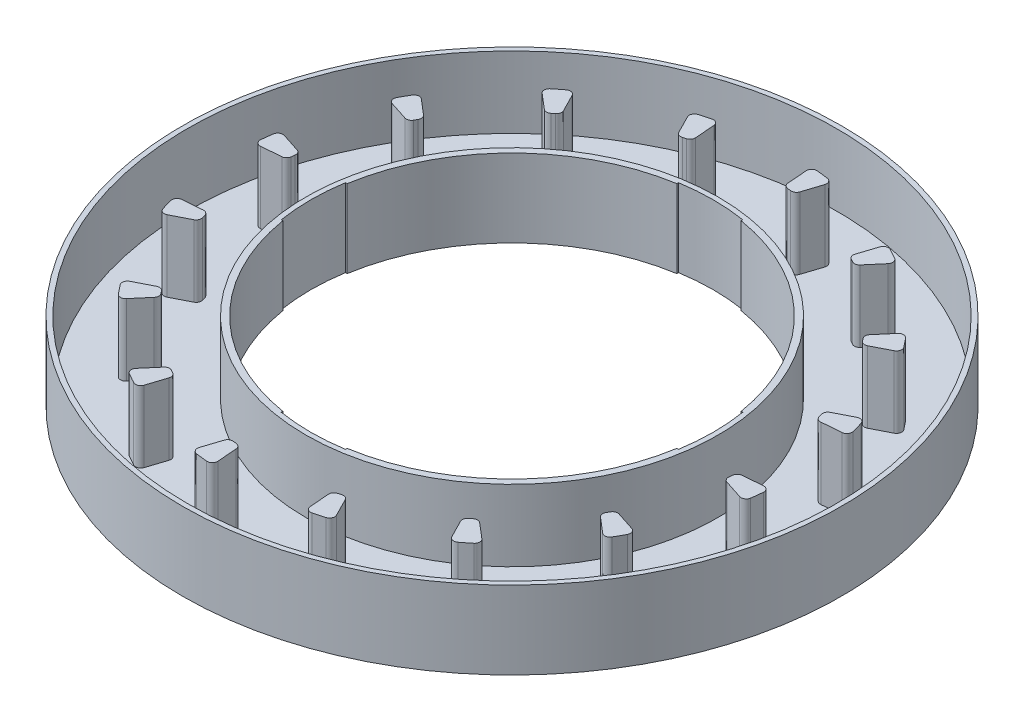
SolidWorks part; units mm, degrees
ref_plane "Front Plane" through (0, 0, 0) normal (0, 0, 1) x (1, 0, 0)
ref_plane "Top Plane" through (0, 0, 0) normal (0, 1, 0) x (1, 0, 0)
ref_plane "Right Plane" through (0, 0, 0) normal (1, 0, 0) x (0, 0, -1)
sketch "Sketch1" plane through (0, 0, 0) normal (0, 1, 0) x (1, 0, 0)
  circle A0 centre (0, 0) radius 61.5
  circle A1 centre (0, 0) radius 101.5
  dimension "D1" = 123
  dimension "D2" = 203
extrude "Boss-Extrude1" add sketch "Sketch1" along normal blind 2
sketch "Sketch2" plane through (0, 2, 0) normal (0, 1, 0) x (1, 0, 0)
  circle A0 centre (0, 0) radius 101.5
  circle A1 centre (0, 0) radius 61.5
  circle A2 centre (0, 0) radius 101.5 construction
  circle A3 centre (0, 0) radius 61.5 construction
  circle A4 centre (0, 0) radius 63.5
  circle A5 centre (0, 0) radius 100
  circle M3 centre (0, 0) radius 101.5
  circle M4 centre (0, 0) radius 61.5
  dimension "D1" = 127
  dimension "D2" = 200
extrude "Boss-Extrude2" add sketch "Sketch2" along normal blind 22 contours A5 M3 | A4 M4
sketch "Sketch3" plane through (0, 0, 0) normal (0, -1, 0) x (1, 0, 0)
  line L0 (-9.8485, 60.7063) -> (-9.9567, 61.1945)
  line L1 (0, 0) -> (0, 124.0373) construction
  line L2 (9.8485, 60.7063) -> (9.9567, 61.1945)
  line L3 (60.7063, -9.8485) -> (61.1945, -9.9567)
  line L4 (60.7063, 9.8485) -> (61.1945, 9.9567)
  line L5 (-9.8485, -60.7063) -> (-9.9567, -61.1945)
  line L6 (9.8485, -60.7063) -> (9.9567, -61.1945)
  line L7 (-60.7063, 9.8485) -> (-61.1945, 9.9567)
  line L8 (-60.7063, -9.8485) -> (-61.1945, -9.9567)
  circle A0 centre (0, 0) radius 61.5 construction
  arc A1 (-9.9567, 61.1945) -> (9.9567, 61.1945) centre (0, 0) cw
  arc A2 (-9.8485, 60.7063) -> (9.8485, 60.7063) centre (0, 0) cw
  arc A3 (60.7063, 9.8485) -> (60.7063, -9.8485) centre (0, 0) cw
  arc A4 (61.1945, 9.9567) -> (61.1945, -9.9567) centre (0, 0) cw
  arc A5 (9.8485, -60.7063) -> (-9.8485, -60.7063) centre (0, 0) cw
  arc A6 (9.9567, -61.1945) -> (-9.9567, -61.1945) centre (0, 0) cw
  arc A7 (-60.7063, -9.8485) -> (-60.7063, 9.8485) centre (0, 0) cw
  arc A8 (-61.1945, -9.9567) -> (-61.1945, 9.9567) centre (0, 0) cw
  point P25 (0, 0)
  dimension "D1" = 25
  dimension "D2" = 20
  dimension "D4" = 4
  dimension "D3" = 0.5
extrude "Cut-Extrude1" cut sketch "Sketch3" against normal through all both and the other way through all
sketch "Sketch4" plane through (0, 2, 0) normal (0, 1, 0) x (1, 0, 0)
  line L2 (64.0409, 54.7617) -> (60.0822, 50.1192)
  line L3 (62.6863, 46.8212) -> (68.1203, 49.5954)
  line L4 (38.2097, 75.1006) -> (36.3289, 69.2965)
  line L5 (39.9969, 67.2462) -> (43.9556, 71.8887)
  line L6 (38.2097, 75.1006) -> (36.3289, 69.2965)
  line L7 (39.9969, 67.2462) -> (43.9556, 71.8887)
  line L8 (80.1225, 26.0858) -> (74.6885, 23.3116)
  line L9 (75.8323, 19.2681) -> (81.9143, 19.7516)
  line L10 (84.0061, -6.5614) -> (77.9241, -7.0449)
  line L11 (77.4335, -11.2183) -> (83.2376, -13.0991)
  line L12 (75.1006, -38.2097) -> (69.2965, -36.3289)
  line L13 (67.2462, -39.9969) -> (71.8887, -43.9556)
  line L14 (54.7617, -64.0409) -> (50.1192, -60.0822)
  line L15 (46.8212, -62.6863) -> (49.5954, -68.1203)
  line L16 (26.0858, -80.1225) -> (23.3116, -74.6885)
  line L17 (19.2681, -75.8323) -> (19.7516, -81.9143)
  line L18 (-6.5614, -84.0061) -> (-7.0449, -77.9241)
  line L19 (-11.2183, -77.4335) -> (-13.0991, -83.2376)
  line L20 (-38.2097, -75.1006) -> (-36.3289, -69.2965)
  line L21 (-39.9969, -67.2462) -> (-43.9556, -71.8887)
  line L22 (-64.0409, -54.7617) -> (-60.0822, -50.1192)
  line L23 (-62.6863, -46.8212) -> (-68.1203, -49.5954)
  line L24 (-80.1225, -26.0858) -> (-74.6885, -23.3116)
  line L25 (-75.8323, -19.2681) -> (-81.9143, -19.7516)
  line L26 (-84.0061, 6.5614) -> (-77.9241, 7.0449)
  line L27 (-77.4335, 11.2183) -> (-83.2376, 13.0991)
  line L28 (-75.1006, 38.2097) -> (-69.2965, 36.3289)
  line L29 (-67.2462, 39.9969) -> (-71.8887, 43.9556)
  line L30 (-54.7617, 64.0409) -> (-50.1192, 60.0822)
  line L31 (-46.8212, 62.6863) -> (-49.5954, 68.1203)
  line L32 (-26.0858, 80.1225) -> (-23.3116, 74.6885)
  line L33 (-19.2681, 75.8323) -> (-19.7516, 81.9143)
  line L34 (6.5614, 84.0061) -> (7.0449, 77.9241)
  line L35 (11.2183, 77.4335) -> (13.0991, 83.2376)
  arc A6 (68.1203, 49.5954) -> (68.6689, 51.9857) centre (67.3928, 51.0204) ccw
  arc A7 (68.6689, 51.9857) -> (66.4933, 54.7409) centre (1.199, 0.9467) ccw
  arc A8 (66.4933, 54.7409) -> (64.0409, 54.7617) centre (65.2584, 53.7235) ccw
  arc A9 (60.0822, 50.1192) -> (60.0508, 48.0808) centre (61.2997, 49.081) ccw
  arc A10 (60.6963, 47.2634) -> (60.0508, 48.0808) centre (1.199, 0.9467) ccw
  arc A11 (60.6963, 47.2634) -> (62.6863, 46.8212) centre (61.9588, 48.2462) ccw
  arc A12 (43.9556, 71.8887) -> (43.5477, 74.307) centre (42.7382, 72.9269) ccw
  arc A13 (43.5477, 74.307) -> (40.4833, 76.0199) centre (0.7454, 1.3335) ccw
  arc A14 (40.4833, 76.0199) -> (38.2097, 75.1006) centre (39.7318, 74.6074) ccw
  arc A15 (36.3289, 69.2965) -> (37.08, 67.4013) centre (37.851, 68.8033) ccw
  arc A16 (37.9891, 66.8931) -> (37.08, 67.4013) centre (0.7454, 1.3335) ccw
  arc A17 (37.9891, 66.8931) -> (39.9969, 67.2462) centre (38.7794, 68.2843) ccw
  arc A18 (43.9556, 71.8887) -> (43.5477, 74.307) centre (42.7382, 72.9269) ccw
  arc A19 (43.5477, 74.307) -> (40.4833, 76.0199) centre (0.7454, 1.3335) ccw
  arc A20 (40.4833, 76.0199) -> (38.2097, 75.1006) centre (39.7318, 74.6074) ccw
  arc A21 (36.3289, 69.2965) -> (37.08, 67.4013) centre (37.851, 68.8033) ccw
  arc A22 (37.9891, 66.8931) -> (37.08, 67.4013) centre (0.7454, 1.3335) ccw
  arc A23 (37.9891, 66.8931) -> (39.9969, 67.2462) centre (38.7794, 68.2843) ccw
  arc A24 (81.9143, 19.7516) -> (83.3358, 21.7501) centre (81.7875, 21.3466) ccw
  arc A25 (83.3358, 21.7501) -> (82.3802, 25.1281) centre (1.47, 0.4158) ccw
  arc A26 (82.3802, 25.1281) -> (80.1225, 26.0858) centre (80.85, 24.6608) ccw
  arc A27 (74.6885, 23.3116) -> (73.8795, 21.4404) centre (75.416, 21.8866) ccw
  arc A28 (74.163, 20.4382) -> (73.8795, 21.4404) centre (1.47, 0.4158) ccw
  arc A29 (74.163, 20.4382) -> (75.8323, 19.2681) centre (75.7055, 20.8631) ccw
  arc A30 (83.2376, -13.0991) -> (85.3157, -11.7968) centre (83.7308, -11.577) ccw
  arc A31 (85.3157, -11.7968) -> (85.7255, -8.3102) centre (1.5173, -0.1784) ccw
  arc A32 (85.7255, -8.3102) -> (84.0061, -6.5614) centre (84.1329, -8.1564) ccw
  arc A33 (77.9241, -7.0449) -> (76.4606, -8.4641) centre (78.0509, -8.6399) ccw
  arc A34 (76.339, -9.4985) -> (76.4606, -8.4641) centre (1.5173, -0.1784) ccw
  arc A35 (76.339, -9.4985) -> (77.4335, -11.2183) centre (77.9267, -9.6962) ccw
  arc A36 (71.8887, -43.9556) -> (74.307, -43.5477) centre (72.9269, -42.7382) ccw
  arc A37 (74.307, -43.5477) -> (76.0199, -40.4833) centre (1.3335, -0.7454) ccw
  arc A38 (76.0199, -40.4833) -> (75.1006, -38.2097) centre (74.6074, -39.7318) ccw
  arc A39 (69.2965, -36.3289) -> (67.4013, -37.08) centre (68.8033, -37.851) ccw
  arc A40 (66.8931, -37.9891) -> (67.4013, -37.08) centre (1.3335, -0.7454) ccw
  arc A41 (66.8931, -37.9891) -> (67.2462, -39.9969) centre (68.2843, -38.7794) ccw
  arc A42 (49.5954, -68.1203) -> (51.9857, -68.6689) centre (51.0204, -67.3928) ccw
  arc A43 (51.9857, -68.6689) -> (54.7409, -66.4933) centre (0.9467, -1.199) ccw
  arc A44 (54.7409, -66.4933) -> (54.7617, -64.0409) centre (53.7235, -65.2584) ccw
  arc A45 (50.1192, -60.0822) -> (48.0808, -60.0508) centre (49.081, -61.2997) ccw
  arc A46 (47.2634, -60.6963) -> (48.0808, -60.0508) centre (0.9467, -1.199) ccw
  arc A47 (47.2634, -60.6963) -> (46.8212, -62.6863) centre (48.2462, -61.9588) ccw
  arc A48 (19.7516, -81.9143) -> (21.7501, -83.3358) centre (21.3466, -81.7875) ccw
  arc A49 (21.7501, -83.3358) -> (25.1281, -82.3802) centre (0.4158, -1.47) ccw
  arc A50 (25.1281, -82.3802) -> (26.0858, -80.1225) centre (24.6608, -80.85) ccw
  arc A51 (23.3116, -74.6885) -> (21.4404, -73.8795) centre (21.8866, -75.416) ccw
  arc A52 (20.4382, -74.163) -> (21.4404, -73.8795) centre (0.4158, -1.47) ccw
  arc A53 (20.4382, -74.163) -> (19.2681, -75.8323) centre (20.8631, -75.7055) ccw
  arc A54 (-13.0991, -83.2376) -> (-11.7968, -85.3157) centre (-11.577, -83.7308) ccw
  arc A55 (-11.7968, -85.3157) -> (-8.3102, -85.7255) centre (-0.1784, -1.5173) ccw
  arc A56 (-8.3102, -85.7255) -> (-6.5614, -84.0061) centre (-8.1564, -84.1329) ccw
  arc A57 (-7.0449, -77.9241) -> (-8.4641, -76.4606) centre (-8.6399, -78.0509) ccw
  arc A58 (-9.4985, -76.339) -> (-8.4641, -76.4606) centre (-0.1784, -1.5173) ccw
  arc A59 (-9.4985, -76.339) -> (-11.2183, -77.4335) centre (-9.6962, -77.9267) ccw
  arc A60 (-43.9556, -71.8887) -> (-43.5477, -74.307) centre (-42.7382, -72.9269) ccw
  arc A61 (-43.5477, -74.307) -> (-40.4833, -76.0199) centre (-0.7454, -1.3335) ccw
  arc A62 (-40.4833, -76.0199) -> (-38.2097, -75.1006) centre (-39.7318, -74.6074) ccw
  arc A63 (-36.3289, -69.2965) -> (-37.08, -67.4013) centre (-37.851, -68.8033) ccw
  arc A64 (-37.9891, -66.8931) -> (-37.08, -67.4013) centre (-0.7454, -1.3335) ccw
  arc A65 (-37.9891, -66.8931) -> (-39.9969, -67.2462) centre (-38.7794, -68.2843) ccw
  arc A66 (-68.1203, -49.5954) -> (-68.6689, -51.9857) centre (-67.3928, -51.0204) ccw
  arc A67 (-68.6689, -51.9857) -> (-66.4933, -54.7409) centre (-1.199, -0.9467) ccw
  arc A68 (-66.4933, -54.7409) -> (-64.0409, -54.7617) centre (-65.2584, -53.7235) ccw
  arc A69 (-60.0822, -50.1192) -> (-60.0508, -48.0808) centre (-61.2997, -49.081) ccw
  arc A70 (-60.6963, -47.2634) -> (-60.0508, -48.0808) centre (-1.199, -0.9467) ccw
  arc A71 (-60.6963, -47.2634) -> (-62.6863, -46.8212) centre (-61.9588, -48.2462) ccw
  arc A72 (-81.9143, -19.7516) -> (-83.3358, -21.7501) centre (-81.7875, -21.3466) ccw
  arc A73 (-83.3358, -21.7501) -> (-82.3802, -25.1281) centre (-1.47, -0.4158) ccw
  arc A74 (-82.3802, -25.1281) -> (-80.1225, -26.0858) centre (-80.85, -24.6608) ccw
  arc A75 (-74.6885, -23.3116) -> (-73.8795, -21.4404) centre (-75.416, -21.8866) ccw
  arc A76 (-74.163, -20.4382) -> (-73.8795, -21.4404) centre (-1.47, -0.4158) ccw
  arc A77 (-74.163, -20.4382) -> (-75.8323, -19.2681) centre (-75.7055, -20.8631) ccw
  arc A78 (-83.2376, 13.0991) -> (-85.3157, 11.7968) centre (-83.7308, 11.577) ccw
  arc A79 (-85.3157, 11.7968) -> (-85.7255, 8.3102) centre (-1.5173, 0.1784) ccw
  arc A80 (-85.7255, 8.3102) -> (-84.0061, 6.5614) centre (-84.1329, 8.1564) ccw
  arc A81 (-77.9241, 7.0449) -> (-76.4606, 8.4641) centre (-78.0509, 8.6399) ccw
  arc A82 (-76.339, 9.4985) -> (-76.4606, 8.4641) centre (-1.5173, 0.1784) ccw
  arc A83 (-76.339, 9.4985) -> (-77.4335, 11.2183) centre (-77.9267, 9.6962) ccw
  arc A84 (-71.8887, 43.9556) -> (-74.307, 43.5477) centre (-72.9269, 42.7382) ccw
  arc A85 (-74.307, 43.5477) -> (-76.0199, 40.4833) centre (-1.3335, 0.7454) ccw
  arc A86 (-76.0199, 40.4833) -> (-75.1006, 38.2097) centre (-74.6074, 39.7318) ccw
  arc A87 (-69.2965, 36.3289) -> (-67.4013, 37.08) centre (-68.8033, 37.851) ccw
  arc A88 (-66.8931, 37.9891) -> (-67.4013, 37.08) centre (-1.3335, 0.7454) ccw
  arc A89 (-66.8931, 37.9891) -> (-67.2462, 39.9969) centre (-68.2843, 38.7794) ccw
  arc A90 (-49.5954, 68.1203) -> (-51.9857, 68.6689) centre (-51.0204, 67.3928) ccw
  arc A91 (-51.9857, 68.6689) -> (-54.7409, 66.4933) centre (-0.9467, 1.199) ccw
  arc A92 (-54.7409, 66.4933) -> (-54.7617, 64.0409) centre (-53.7235, 65.2584) ccw
  arc A93 (-50.1192, 60.0822) -> (-48.0808, 60.0508) centre (-49.081, 61.2997) ccw
  arc A94 (-47.2634, 60.6963) -> (-48.0808, 60.0508) centre (-0.9467, 1.199) ccw
  arc A95 (-47.2634, 60.6963) -> (-46.8212, 62.6863) centre (-48.2462, 61.9588) ccw
  arc A96 (-19.7516, 81.9143) -> (-21.7501, 83.3358) centre (-21.3466, 81.7875) ccw
  arc A97 (-21.7501, 83.3358) -> (-25.1281, 82.3802) centre (-0.4158, 1.47) ccw
  arc A98 (-25.1281, 82.3802) -> (-26.0858, 80.1225) centre (-24.6608, 80.85) ccw
  arc A99 (-23.3116, 74.6885) -> (-21.4404, 73.8795) centre (-21.8866, 75.416) ccw
  arc A100 (-20.4382, 74.163) -> (-21.4404, 73.8795) centre (-0.4158, 1.47) ccw
  arc A101 (-20.4382, 74.163) -> (-19.2681, 75.8323) centre (-20.8631, 75.7055) ccw
  arc A102 (13.0991, 83.2376) -> (11.7968, 85.3157) centre (11.577, 83.7308) ccw
  arc A103 (11.7968, 85.3157) -> (8.3102, 85.7255) centre (0.1784, 1.5173) ccw
  arc A104 (8.3102, 85.7255) -> (6.5614, 84.0061) centre (8.1564, 84.1329) ccw
  arc A105 (7.0449, 77.9241) -> (8.4641, 76.4606) centre (8.6399, 78.0509) ccw
  arc A106 (9.4985, 76.339) -> (8.4641, 76.4606) centre (0.1784, 1.5173) ccw
  arc A107 (9.4985, 76.339) -> (11.2183, 77.4335) centre (9.6962, 77.9267) ccw
  point P227 (0, 0)
  dimension "D1" = 0.4
  dimension "D2" = 16
extrude "Boss-Extrude3" add sketch "Sketch4" along normal blind 22 contours A106 A107 L35 A102 A103 A104 L34 A105 | A100 A101 L33 A96 A97 A98 L32 A99 | A94 A95 L31 A90 A91 A92 L30 A93 | A88 A89 L29 A84 A85 A86 L28 A87 | A10 A11 L3 A6 A7 A8 L2 A9 | A28 A29 L9 A24 A25 A26 L8 A27 | A76 A77 L25 A72 A73 A74 L24 A75 | A70 A71 L23 A66 A67 A68 L22 A69 | A34 A35 L11 A30 A31 A32 L10 A33 | A40 A41 L13 A36 A37 A38 L12 A39 | A64 A65 L21 A60 A61 A62 L20 A63 | A58 A59 L19 A54 A55 A56 L18 A57 | A52 A53 L17 A48 A49 A50 L16 A51 | A18 A19 A20 L6 A21 A22 A23 L7 | L27 A78 A79 A80 L26 A81 A82 A83 | L15 A42 A43 A44 L14 A45 A46 A47
